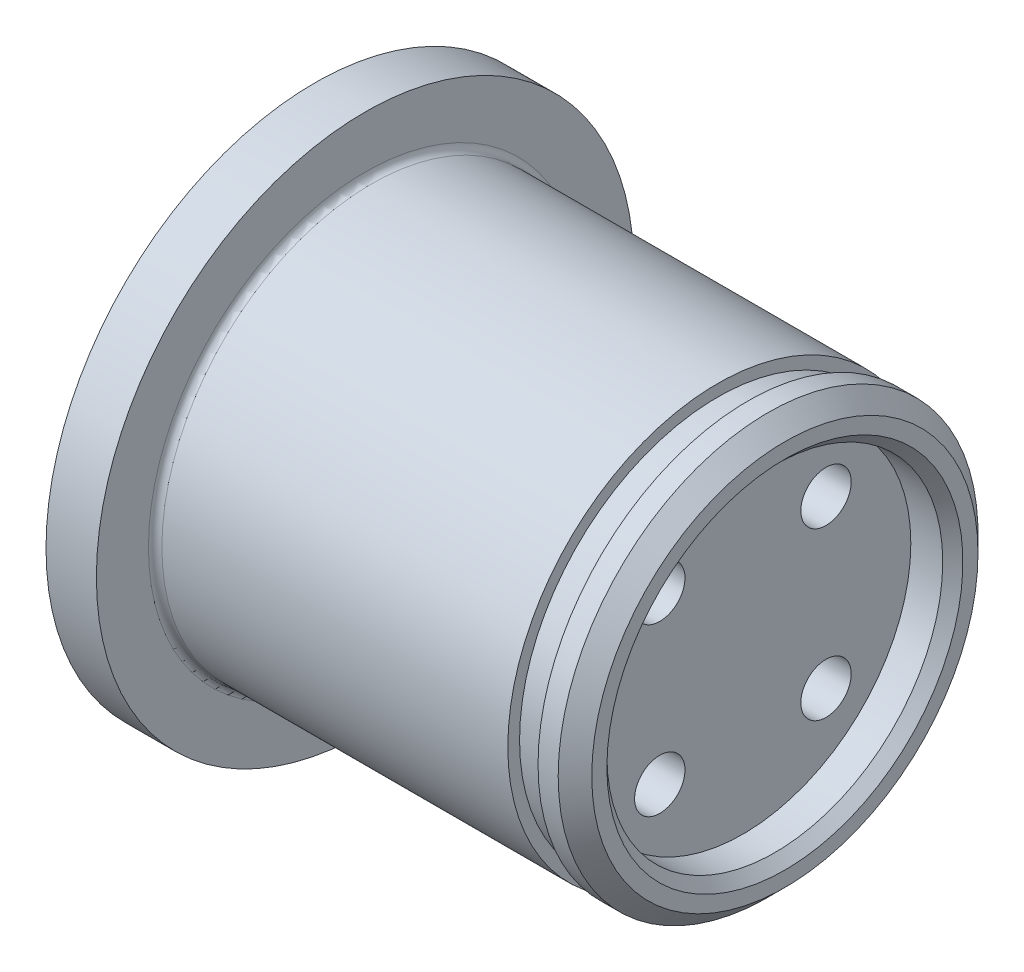
SolidWorks part; units mm, degrees
ref_plane "Спереди" through (0, 0, 0) normal (0, 0, 1) x (1, 0, 0)
ref_plane "Сверху" through (0, 0, 0) normal (0, 1, 0) x (1, 0, 0)
ref_plane "Справа" through (0, 0, 0) normal (1, 0, 0) x (0, 0, -1)
sketch "Эскиз1" plane through (0, 0, 0) normal (0, 0, 1) x (1, 0, 0)
  line L0 (0, 0) -> (22138.4448, 0) construction
  line L1 (0, 0) -> (0, 12.5)
  line L2 (0, 12.5) -> (-25, 12.5)
  line L3 (-25, 12.5) -> (-25, 16)
  line L4 (-25, 16) -> (-28, 16)
  line L5 (-28, 16) -> (-28, 0)
  line L8 (0, 0) -> (-28, 0)
  dimension "D1" = 28
  dimension "D2" = 3
  dimension "D3" = 25
  dimension "D6" = 32
revolve "Повернуть1" add sketch "Эскиз1" angle 360 about L0
sketch "Эскиз2" plane through (0, 0, 0) normal (0, 0, 1) x (1, 0, 0)
  line L0 (-4, 12.5) -> (-4, 11.8)
  line L1 (0, 12.5) -> (-25, 12.5) construction
  line L2 (-4, 11.8) -> (-2.2, 11.8)
  line L3 (-2.2, 11.8) -> (-2.2, 12.5)
  line L4 (-2.2, 12.5) -> (-4, 12.5)
  line L5 (0, -12.5) -> (0, 12.5) construction
  line L6 (0, 0) -> (-50000, 0) construction
  point P10 (-2.2, 12.15)
  point P13 (0, 0)
  dimension "D1" = 4
  dimension "D2" = 1.8
  dimension "D3" = 23.6
revolve "Вырез-Повернуть1" cut sketch "Эскиз2" angle 360 about L6
chamfer "Фаска1" distance 1 angle 45 1 edges at (0, 0, 12.5)
fillet "Скругление1" radius 0.4 1 edges at (-25, 0, 12.5)
hole_wizard "Отверстие1" positions "Эскиз3" profile "Эскиз4" legacy end condition through all
sketch "Эскиз3" plane through (0, 0, 0) normal (1, 0, 0) x (0, 0, -1)
  line L0 (0, 0) -> (0, 7) construction
  line L2 (0, 0) -> (4.9497, 4.9497) construction
  circle A0 centre (0, 0) radius 7 construction
  point P0 (4.9497, 4.9497)
  dimension "D1" = 14
  dimension "D2" = 45
sketch "Эскиз4" plane through (0, 4.9497, -4.9497) normal (0, 1, 0) x (0, 0, -1)
  line L0 (0, 0) -> (0, 28)
  line L1 (0, 28) -> (1.5, 28)
  line L2 (1.5, 28) -> (1.5, 0)
  line L3 (1.5, 0) -> (0, 0)
  line L4 (0, 110) -> (0, -10) construction
  dimension "Диаметр" = 3
  dimension "Глубина" = 28
pattern_circular "Круговой массив1" count 4 over 360 about axis through (0, 0, 0) along (1, 0, 0) of "Отверстие1"
sketch "Эскиз5" plane through (0, 0, 0) normal (0, 0, 1) x (1, 0, 0)
  line L0 (0, 0) -> (0, 10)
  line L1 (0, -11.5) -> (0, 11.5) construction
  line L7 (0, 10) -> (-2.5, 10)
  line L8 (-2.5, 10) -> (-2.5, 0)
  line L9 (-2.5, 0) -> (0, 0)
  line L10 (0, 0) -> (-50000, 0) construction
  dimension "D1" = 2.5
  dimension "D2" = 20
revolve "Вырез-Повернуть2" cut sketch "Эскиз5" angle 360 about L10
chamfer "Фаска2" distance 0.6 angle 45 1 edges at (0, 0, -10)
